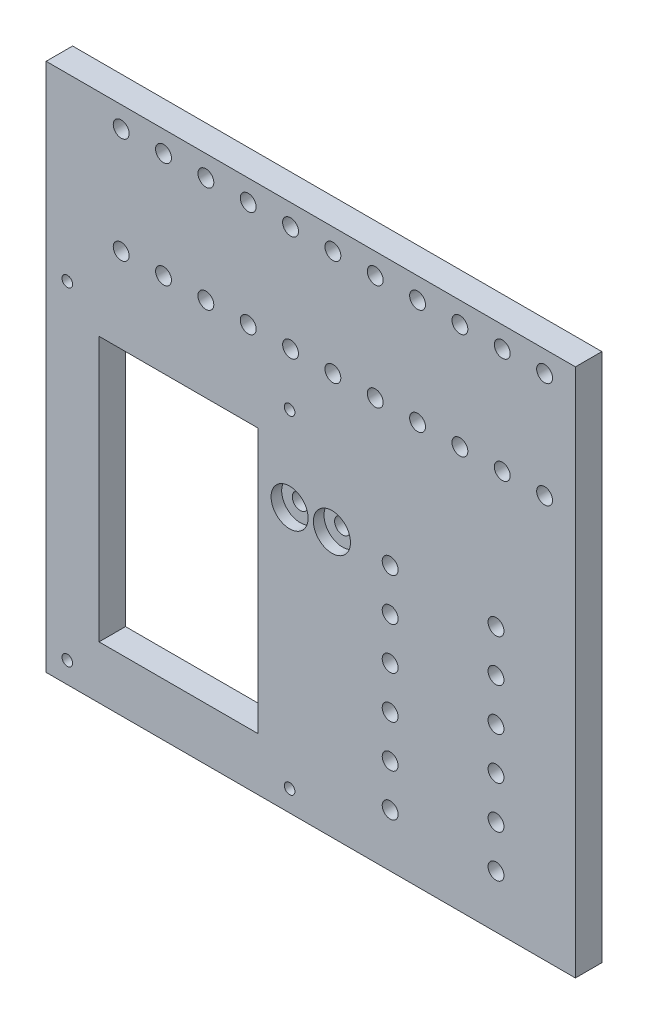
SolidWorks part; units mm, degrees
ref_plane "前视基准面" through (0, 0, 0) normal (0, 0, 1) x (1, 0, 0)
ref_plane "上视基准面" through (0, 0, 0) normal (0, 1, 0) x (1, 0, 0)
ref_plane "右视基准面" through (0, 0, 0) normal (1, 0, 0) x (0, 0, -1)
sketch "草图1" plane through (0, 0, 0) normal (0, 0, 1) x (1, 0, 0)
  line L0 (0, -4) -> (0, 4) construction
  line L1 (-8, 0) -> (8, 0) construction
  line L3 (-50, 50) -> (50, 50)
  line L4 (-50, 50) -> (-50, -50)
  line L5 (-50, -50) -> (50, -50)
  line L6 (50, 50) -> (50, -50)
  line L7 (-50, 50) -> (50, -50) construction
  line L8 (-50, -50) -> (50, 50) construction
  circle A0 centre (-4, 0) radius 1.5
  circle A1 centre (4, 0) radius 1.5
  point P4 (0, 0)
  point P8 (0, 0)
  point P11 (0, 0)
  dimension "D3" = 3
  dimension "D4" = 4
  dimension "D1" = 8
  dimension "D2" = 16
  dimension "D5" = 100
  dimension "D6" = 100
extrude "凸台-拉伸1" add sketch "草图1" along normal blind 5
sketch "草图2" plane through (0, 0, 5) normal (0, 0, 1) x (1, 0, 0)
  line L2 (-19.2684, 0) -> (19.2684, 0) construction
  circle A3 centre (-46, -46) radius 1
  circle A28 centre (-46, 16) radius 1
  circle A29 centre (-4, -46) radius 1
  circle A30 centre (-4, 16) radius 1
  point P9 (0, 0)
  point P10 (0, 0)
  point P14 (0, 0)
  point P39 (0, 0)
  point P54 (0, 0)
  point P71 (0, 0)
  dimension "D1" = 62
  dimension "D2" = 42
  dimension "D9" = 42
extrude "切除-拉伸1" cut sketch "草图2" against normal through all
sketch "草图3" plane through (0, 0, 5) normal (0, 0, 1) x (1, 0, 0)
  circle A0 centre (-4, 0) radius 3.5
  circle A1 centre (4, 0) radius 3.5
  dimension "D1" = 7
  dimension "D2" = 7
extrude "切除-拉伸2" cut sketch "草图3" against normal blind 2
sketch "草图4" plane through (0, 0, 5) normal (0, 0, 1) x (1, 0, 0)
  line L0 (0, -50) -> (0, 50) construction
  line L1 (50, 50) -> (-50, 50) construction
  line L2 (-50, 0) -> (50, 0) construction
  line L3 (50, -50) -> (50, 50) construction
  line L4 (50, -50) -> (0, -50) construction
  line L5 (25, 50) -> (25, -50) construction
  line L6 (50, 50) -> (-50, 50) construction
  line L7 (35, 0) -> (15, 0) construction
  circle A0 centre (35, 0) radius 1.5
  circle A1 centre (15, 0) radius 1.5
  circle A2 centre (35, -8) radius 1.5
  circle A3 centre (15, -8) radius 1.5
  circle A4 centre (35, -16) radius 1.5
  circle A5 centre (15, -16) radius 1.5
  circle A6 centre (35, -24) radius 1.5
  circle A7 centre (15, -24) radius 1.5
  circle A8 centre (35, -32) radius 1.5
  circle A9 centre (15, -32) radius 1.5
  circle A10 centre (35, -40) radius 1.5
  circle A11 centre (15, -40) radius 1.5
  point P6 (0, 0)
  point P11 (0, 0)
  point P20 (25, 0)
  dimension "D2" = 3
  dimension "D3" = 3
  dimension "D1" = 20
  dimension "D4" = 6
extrude "切除-拉伸3" cut sketch "草图4" against normal blind 10
sketch "草图5" plane through (0, 0, 0) normal (0, 0, -1) x (-1, 0, 0)
  line L0 (0, 0) -> (0, 50) construction
  line L1 (-50, 50) -> (50, 50) construction
  line L2 (0, 36) -> (35.8217, 36) construction
  line L3 (35.8217, 46) -> (35.8217, 26) construction
  circle A0 centre (4, 16) radius 1 construction
  circle A1 centre (35.8217, 46) radius 1.5
  circle A2 centre (35.8217, 26) radius 1.5
  circle A3 centre (27.8217, 46) radius 1.5
  circle A4 centre (27.8217, 26) radius 1.5
  circle A5 centre (19.8217, 46) radius 1.5
  circle A6 centre (19.8217, 26) radius 1.5
  circle A7 centre (11.8217, 46) radius 1.5
  circle A8 centre (11.8217, 26) radius 1.5
  circle A9 centre (3.8217, 46) radius 1.5
  circle A10 centre (3.8217, 26) radius 1.5
  circle A11 centre (-4.1783, 46) radius 1.5
  circle A12 centre (-4.1783, 26) radius 1.5
  circle A13 centre (-12.1783, 46) radius 1.5
  circle A14 centre (-12.1783, 26) radius 1.5
  circle A15 centre (-20.1783, 46) radius 1.5
  circle A16 centre (-20.1783, 26) radius 1.5
  circle A17 centre (-28.1783, 46) radius 1.5
  circle A18 centre (-28.1783, 26) radius 1.5
  circle A19 centre (-36.1783, 46) radius 1.5
  circle A20 centre (-36.1783, 26) radius 1.5
  circle A21 centre (-44.1783, 46) radius 1.5
  circle A22 centre (-44.1783, 26) radius 1.5
  point P12 (35.8217, 36)
  dimension "D3" = 3
  dimension "D4" = 3
  dimension "D1" = 20
  dimension "D2" = 20
  dimension "D5" = 11
extrude "切除-拉伸4" cut sketch "草图5" against normal blind 10
sketch "草图6" plane through (0, 0, 0) normal (0, 0, -1) x (-1, 0, 0)
  line L1 (10, 10) -> (40, 10)
  line L2 (10, 10) -> (10, -40)
  line L3 (10, -40) -> (40, -40)
  line L4 (40, 10) -> (40, -40)
  circle A0 centre (4, 0) radius 1.5 construction
  circle A1 centre (46, 16) radius 1 construction
  circle A2 centre (4, -46) radius 1 construction
  dimension "D1" = 6
  dimension "D2" = 6
  dimension "D3" = 6
  dimension "D4" = 6
extrude "切除-拉伸5" cut sketch "草图6" against normal blind 10
